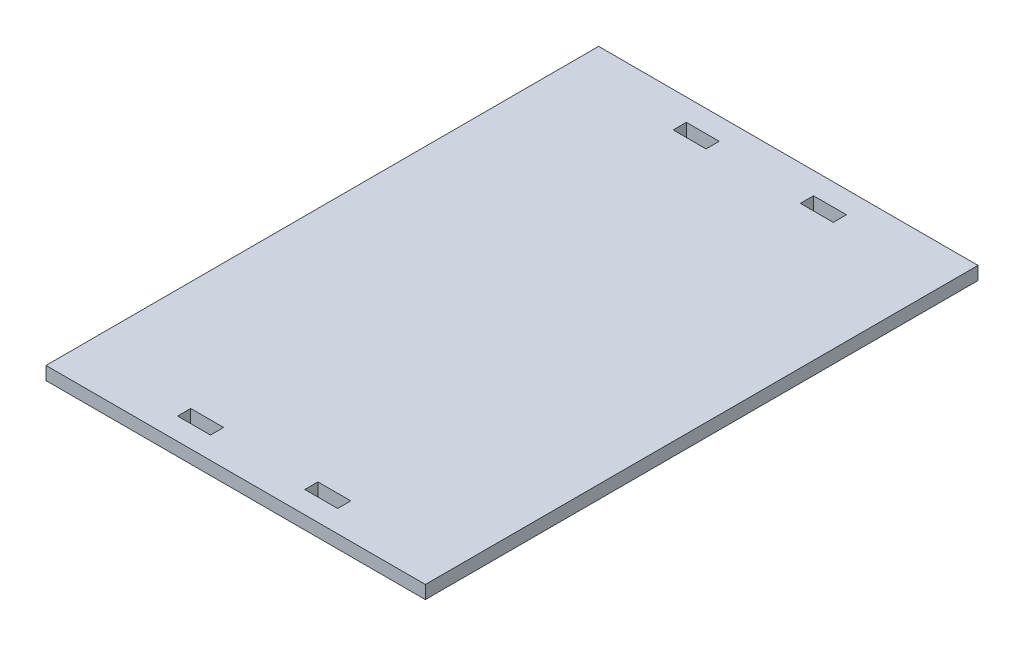
SolidWorks part; units mm, degrees
ref_plane "Front Plane" through (0, 0, 0) normal (0, 0, 1) x (1, 0, 0)
ref_plane "Top Plane" through (0, 0, 0) normal (0, 1, 0) x (1, 0, 0)
ref_plane "Right Plane" through (0, 0, 0) normal (1, 0, 0) x (0, 0, -1)
sketch "Sketch1" plane through (0, 0, 0) normal (0, 1, 0) x (1, 0, 0)
  line L0 (0, 0) -> (-173, 0)
  line L1 (-173, 0) -> (-173, -252)
  line L3 (-108, -10) -> (-108, -16)
  line L5 (-65, -16) -> (-65, -10)
  line L11 (-108, -236) -> (-108, -242)
  line L14 (-173, -252) -> (0, -252)
  line L17 (-65, -242) -> (-65, -236)
  line L18 (-108, -10) -> (-123, -10)
  line L20 (-123, -10) -> (-123, -16)
  line L22 (-123, -16) -> (-108, -16)
  line L23 (-65, -10) -> (-50, -10)
  line L25 (-50, -10) -> (-50, -16)
  line L27 (-50, -16) -> (-65, -16)
  line L28 (0, -252) -> (0, 0)
  line L29 (-108, -236) -> (-123, -236)
  line L31 (-123, -236) -> (-123, -242)
  line L33 (-123, -242) -> (-108, -242)
  line L34 (-65, -236) -> (-50, -236)
  line L36 (-50, -236) -> (-50, -242)
  line L38 (-50, -242) -> (-65, -242)
  dimension "D1" = 6
  dimension "D2" = 43
  dimension "D3" = 15
  dimension "D4" = 50
  dimension "D5" = 220
  dimension "D6" = 10
  dimension "D7" = 43
  dimension "D8" = 15
  dimension "D9" = 6
  dimension "D10" = 173
  dimension "D12" = 50
  dimension "D14" = 10
extrude "Boss-Extrude1" add sketch "Sketch1" along normal blind 6
